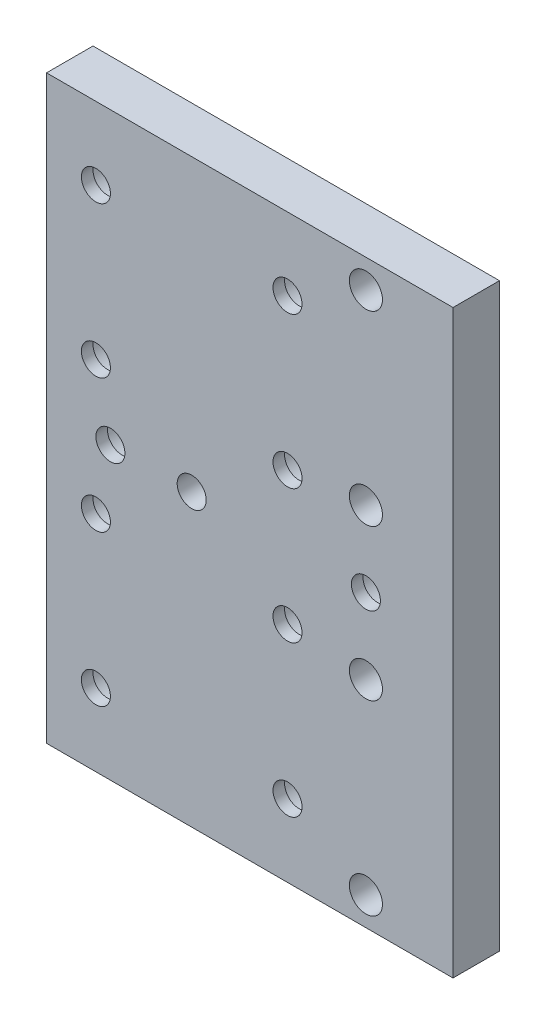
SolidWorks part; units mm, degrees
ref_plane "Ön Düzlem" through (0, 0, 0) normal (0, 0, 1) x (1, 0, 0)
ref_plane "Üst Düzlem" through (0, 0, 0) normal (0, 1, 0) x (1, 0, 0)
ref_plane "Sağ Düzlem" through (0, 0, 0) normal (1, 0, 0) x (0, 0, -1)
sketch "Sketch1" plane through (0, 0, 0) normal (0, 0, 1) x (1, 0, 0)
  line L0 (0, -60) -> (0, 60)
  line L1 (0, 60) -> (-70, 60)
  line L2 (-70, 60) -> (-70, -60)
  line L3 (-70, -60) -> (0, -60)
  line L4 (-45, 24.5) -> (-45, -24.5) construction
  line L11 (-61.5, 11.5) -> (-28.5, 11.5) construction
  line L12 (-61.5, 11.5) -> (-61.5, 37.5) construction
  line L13 (-61.5, 37.5) -> (-28.5, 37.5) construction
  line L14 (-28.5, 11.5) -> (-28.5, 37.5) construction
  line L15 (-61.5, 11.5) -> (-28.5, 37.5) construction
  line L16 (-61.5, 37.5) -> (-28.5, 11.5) construction
  line L17 (-61.5, -37.5) -> (-28.5, -37.5) construction
  line L18 (-61.5, -37.5) -> (-61.5, -11.5) construction
  line L19 (-61.5, -11.5) -> (-28.5, -11.5) construction
  line L20 (-28.5, -37.5) -> (-28.5, -11.5) construction
  line L21 (-61.5, -37.5) -> (-28.5, -11.5) construction
  line L22 (-61.5, -11.5) -> (-28.5, -37.5) construction
  line L25 (-15, 45.1) -> (-15, 13) construction
  line L26 (-15, -13) -> (-15, -45.1) construction
  line L27 (-15, 29.05) -> (-15, -29.05) construction
  circle A5 centre (-61.5, 37.5) radius 2.5
  circle A6 centre (-28.5, 37.5) radius 2.5
  circle A7 centre (-61.5, 11.5) radius 2.5
  circle A8 centre (-28.5, 11.5) radius 2.5
  circle A9 centre (-61.5, -11.5) radius 2.5
  circle A10 centre (-28.5, -11.5) radius 2.5
  circle A11 centre (-28.5, -37.5) radius 2.5
  circle A12 centre (-61.5, -37.5) radius 2.5
  circle A13 centre (-15, 45.1) radius 2.85
  circle A14 centre (-15, 13) radius 2.85
  circle A15 centre (-15, -13) radius 2.85
  circle A16 centre (-15, -45.1) radius 2.85
  point P4 (0, 0)
  point P16 (-45, -24.5)
  point P19 (-45, 24.5)
  point P29 (-45, 0)
  point P51 (-15, 0)
  dimension "D11" = 5
  dimension "D13" = 5.7
  dimension "D16" = 15
  dimension "D1" = 120
  dimension "D2" = 70
  dimension "D7" = 33
  dimension "D8" = 26
  dimension "D9" = 23
  dimension "D10" = 45
  dimension "D12" = 32.1
  dimension "D17" = 26
extrude "Boss-Extrude1" add sketch "Sketch1" along normal blind 8
sketch "Sketch2" plane through (0, 0, 8) normal (0, 0, 1) x (1, 0, 0)
  circle A0 centre (-45, 0) radius 2.5
  dimension "D1" = 5
  dimension "D2" = 45
extrude "Cut-Extrude1" cut sketch "Sketch2" against normal through all
ref_plane "Plane1" through (-70, 60, 0) normal (0, -1, 0) x (-1, 0, 0)
sketch "Sketch4" plane through (0, 0, 0) normal (0, 0, -1) x (-1, 0, 0)
  line L0 (0, 60) -> (70, 60) construction
  line L1 (-19.529, 67.8256) -> (86.6142, 67.8256)
  line L2 (-19.529, 67.8256) -> (-19.529, 50)
  line L3 (-19.529, 50) -> (86.6142, 50)
  line L4 (86.6142, 67.8256) -> (86.6142, 50)
  line L5 (-25.5248, -50) -> (95.365, -50)
  line L6 (-25.5248, -50) -> (-25.5248, -65.7189)
  line L7 (-25.5248, -65.7189) -> (95.365, -65.7189)
  line L8 (95.365, -50) -> (95.365, -65.7189)
  line L9 (70, -60) -> (0, -60) construction
  dimension "D1" = 10
  dimension "D2" = 10
extrude "Cut-Extrude2" cut sketch "Sketch4" against normal through all
sketch "Sketch5" plane through (0, 0, 0) normal (0, 0, -1) x (-1, 0, 0)
  line L0 (0, -50) -> (0, 50) construction
  circle A0 centre (59, 0) radius 2.5
  circle A1 centre (15, 0) radius 2.5
  point P4 (0, 0)
  dimension "D2" = 59
  dimension "D3" = 5
  dimension "D1" = 15
extrude "Cut-Extrude3" cut sketch "Sketch5" against normal through all
sketch "Sketch6" plane through (0, 0, 0) normal (0, 0, -1) x (-1, 0, 0)
  circle A0 centre (28.5, 37.5) radius 4.25
  circle A1 centre (61.5, 37.5) radius 4.25
  circle A2 centre (28.5, 11.5) radius 4.25
  circle A3 centre (61.5, 11.5) radius 4.25
  circle A4 centre (28.5, -11.5) radius 4.25
  circle A5 centre (61.5, -11.5) radius 4.25
  circle A6 centre (61.5, -37.5) radius 4.25
  circle A7 centre (28.5, -37.5) radius 4.25
  dimension "D1" = 8.5
extrude "Cut-Extrude4" cut sketch "Sketch6" against normal blind 6
sketch "Sketch7" plane through (0, 0, 0) normal (0, 0, -1) x (-1, 0, 0)
  circle A0 centre (15, 0) radius 4.25
  circle A1 centre (59, 0) radius 4.25
  dimension "D1" = 8.5
extrude "Cut-Extrude5" cut sketch "Sketch7" against normal blind 6
